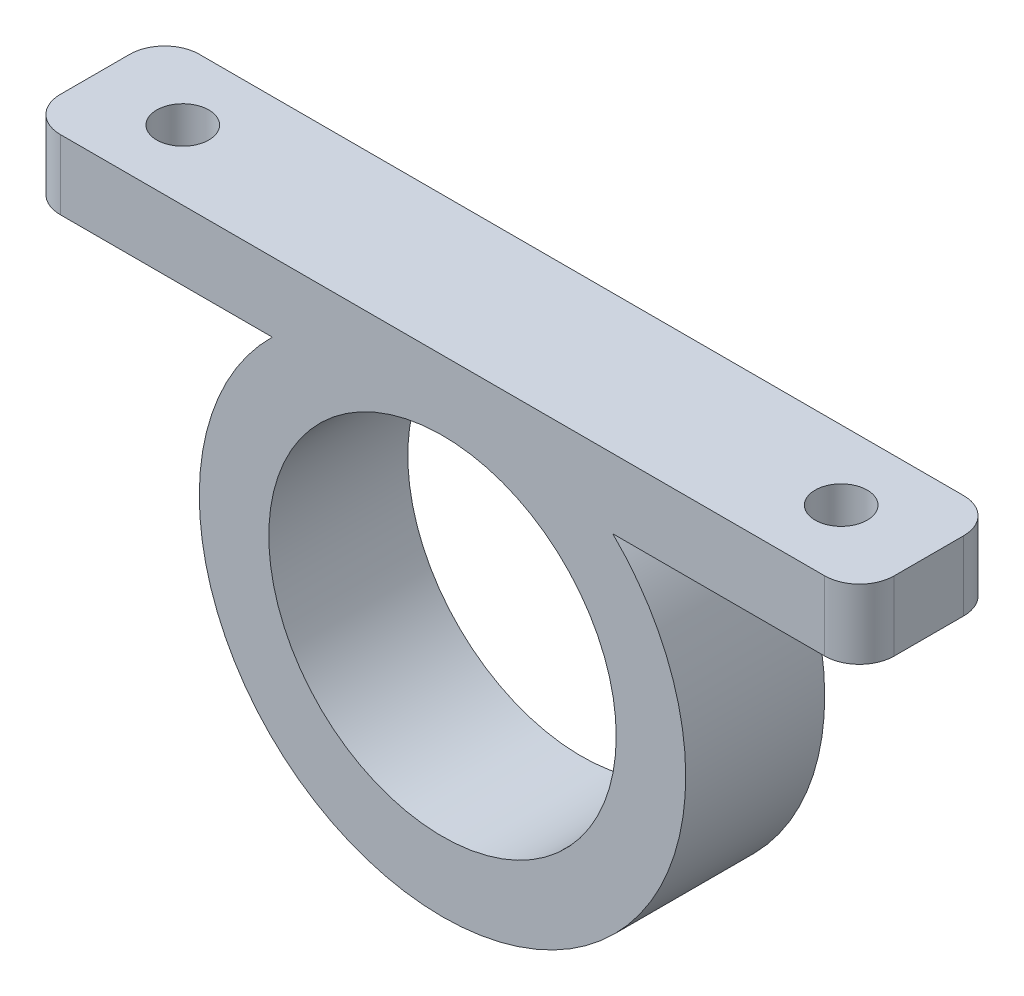
SolidWorks part; units mm, degrees
ref_plane "Alzado" through (0, 0, 0) normal (0, 0, 1) x (1, 0, 0)
ref_plane "Planta" through (0, 0, 0) normal (0, 1, 0) x (1, 0, 0)
ref_plane "Vista lateral" through (0, 0, 0) normal (1, 0, 0) x (0, 0, -1)
sketch "Croquis1" plane through (0, 0, 0) normal (0, 0, 1) x (1, 0, 0)
  line L0 (0, 14) -> (24, 14)
  line L1 (0, 14) -> (-24, 14)
  line L2 (-24, 14) -> (-24, 10)
  line L3 (-24, 10) -> (-9.798, 10)
  line L4 (24, 14) -> (24, 10)
  line L5 (24, 10) -> (9.798, 10)
  circle A0 centre (0, 0) radius 10
  arc A1 (-9.798, 10) -> (9.798, 10) centre (0, 0) ccw
  dimension "D1" = 20
  dimension "D2" = 14
  dimension "D4" = 14
  dimension "D3" = 48
  dimension "D5" = 4
  dimension "D6" = 4
  dimension "D7" = 24
extrude "Saliente-Extruir1" add sketch "Croquis1" along normal blind 8
fillet "Redondeo1" radius 2 4 edges at (24, 12, 8) (24, 12, 0) (-24, 12, 0) (-24, 12, 8)
sketch "Croquis2" plane through (0, 10, 0) normal (0, -1, 0) x (1, 0, 0)
  line L0 (-22, 8) -> (-15.899, 0) construction
  line L1 (-22, 0) -> (-9.798, 0) construction
  line L2 (15.899, 0) -> (22, 8) construction
  line L3 (9.798, 0) -> (22, 0) construction
  circle A0 centre (-18.9495, 4) radius 1.5
  circle A1 centre (18.9495, 4) radius 1.5
  point P14 (0, 0)
  dimension "D1" = 3
  dimension "D2" = 3
extrude "Cortar-Extruir1" cut sketch "Croquis2" against normal through all
